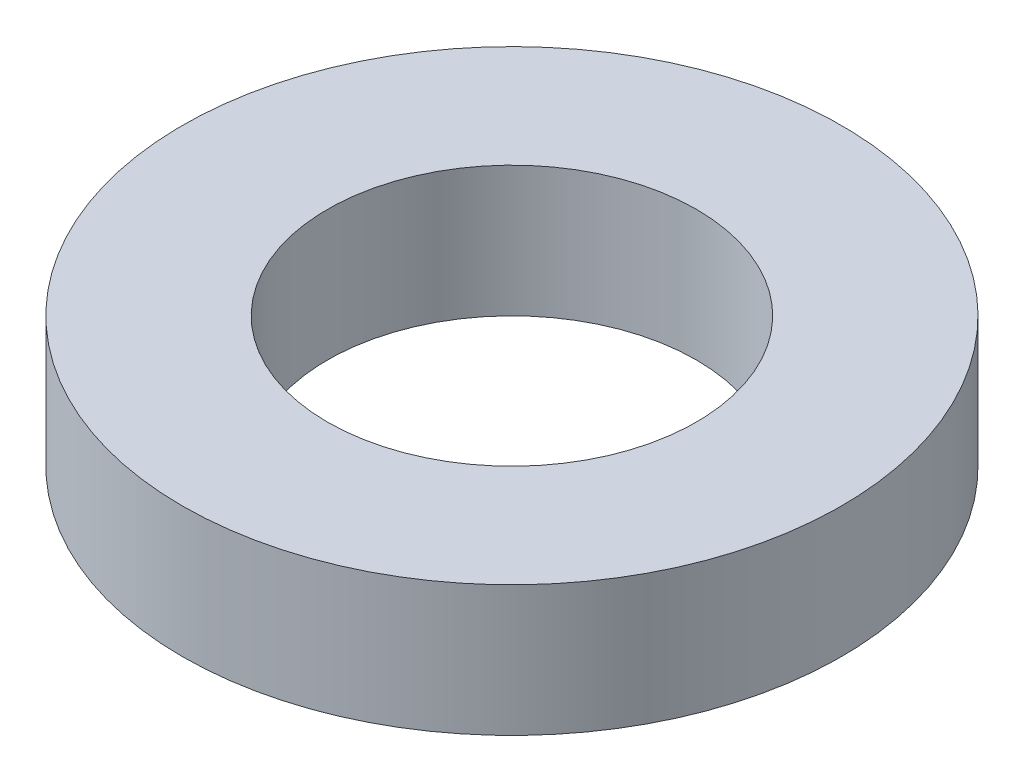
SolidWorks part; units mm, degrees
ref_plane "Front Plane" through (0, 0, 0) normal (0, 0, 1) x (1, 0, 0)
ref_plane "Top Plane" through (0, 0, 0) normal (0, 1, 0) x (1, 0, 0)
ref_plane "Right Plane" through (0, 0, 0) normal (1, 0, 0) x (0, 0, -1)
sketch "Sketch1" plane through (0, 0, 0) normal (0, 1, 0) x (1, 0, 0)
  circle A0 centre (0, 0) radius 126.27
  dimension "D1" = 252.54
extrude "Boss-Extrude1" add sketch "Sketch1" along normal blind 50
sketch "Sketch3" plane through (0, 50, 0) normal (0, 1, 0) x (1, 0, 0)
  circle A0 centre (0, 0) radius 70.6458
extrude "Cut-Extrude1" cut sketch "Sketch3" against normal through all
